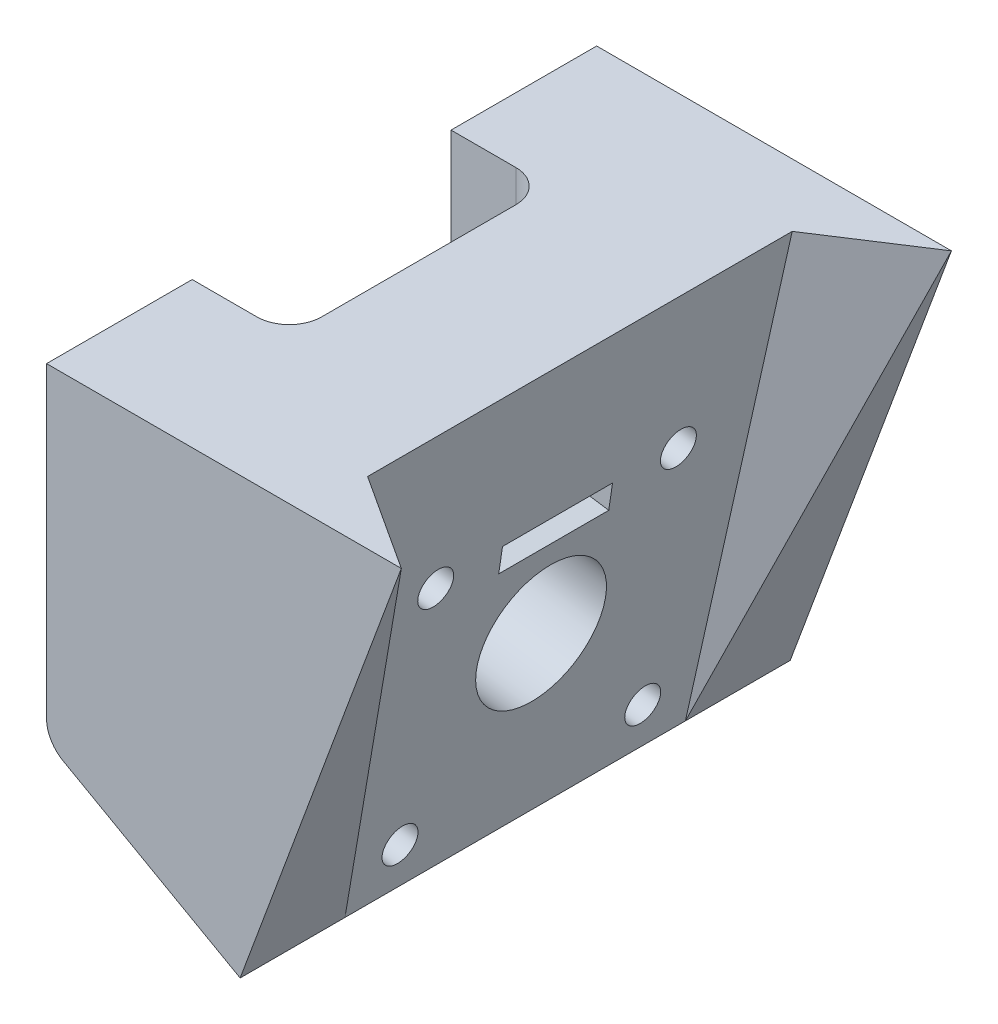
SolidWorks part; units mm, degrees
ref_plane "前视基准面" through (0, 0, 0) normal (0, 0, 1) x (1, 0, 0)
ref_plane "上视基准面" through (0, 0, 0) normal (0, 1, 0) x (1, 0, 0)
ref_plane "右视基准面" through (0, 0, 0) normal (1, 0, 0) x (0, 0, -1)
sketch "草图1" plane through (0, 0, 0) normal (0, 0, 1) x (1, 0, 0)
  line L1 (111.6207, -71.4575) -> (111.6207, -52.4486)
  line L2 (111.6207, -52.4486) -> (139.5487, -52.4486)
  line L4 (139.5487, -52.4486) -> (129.3649, -79.9481)
  line L6 (126.5093, -80.9969) -> (112.6407, -73.2009)
  arc A1 (126.5093, -80.9969) -> (129.3649, -79.9481) centre (127.4894, -79.2535) ccw
  arc A3 (111.6207, -71.4575) -> (112.6407, -73.2009) centre (113.6207, -71.4575) ccw
extrude "凸台-拉伸1" add sketch "草图1" along normal blind 34
sketch "草图2" plane through (0, -52.4486, 0) normal (0, 1, 0) x (1, 0, 0)
  line L0 (129.3649, -34) -> (129.3649, 0) construction
  line L1 (129.3649, -30) -> (129.3649, -4)
  line L3 (129.3649, -4) -> (139.5487, 0)
  line L5 (129.3649, -30) -> (139.5487, -34)
  line L6 (139.5487, -34) -> (139.5487, 0) construction
  line L7 (139.5487, -34) -> (139.5487, 0)
extrude "切除-拉伸1" cut sketch "草图2" against normal blind 34
ref_plane "基准面1" through (0, 0, 17) normal (0, 0, 1) x (1, 0, 0)
sketch "草图14" plane through (0, -52.4486, 0) normal (0, 1, 0) x (1, 0, 0)
  line L0 (111.6207, -17) -> (111.6207, -9)
  line L1 (111.6207, -9) -> (117.6207, -9)
  line L2 (117.6207, -9) -> (117.6207, -25)
  line L3 (117.6207, -25) -> (111.6207, -25)
  line L6 (111.6207, -34) -> (139.5487, -34)
  line L7 (139.5487, -34) -> (129.3649, -30)
  line L8 (129.3649, -30) -> (129.3649, -4)
  line L9 (129.3649, -4) -> (139.5487, 0)
  line L10 (139.5487, 0) -> (111.6207, 0)
  line L11 (111.6207, 0) -> (111.6207, -34)
  line L17 (111.6207, -9) -> (111.6207, -25)
  line M12 (111.6207, 0) -> (111.6207, -34)
  dimension "D1" = 0
extrude "切除-拉伸12" cut sketch "草图14" against normal through all contours L3 L2 L1 M12
fillet "圆角1" radius 2 2 edges at (117.6207, -64.2245, 25) (117.6207, -64.2245, 9)
sketch "草图15" plane through (0, 0, 34) normal (0, 0, 1) x (1, 0, 0)
  line L0 (129.3649, -79.9481) -> (139.5487, -52.4486) construction
  line L1 (129.3649, -79.9481) -> (139.5487, -52.4486)
  line L2 (139.5487, -52.4486) -> (133.5487, -52.4486)
  line L3 (139.5487, -52.4486) -> (111.6207, -52.4486) construction
  line L4 (133.5487, -52.4486) -> (124.3987, -77.1564)
  line L5 (112.6407, -73.2009) -> (126.5093, -80.9969) construction
  line L7 (121.5431, -78.2053) -> (126.5093, -80.9969)
  arc A0 (126.5093, -80.9969) -> (129.3649, -79.9481) centre (127.4894, -79.2535) ccw construction
  arc A1 (126.5093, -80.9969) -> (129.3649, -79.9481) centre (127.4894, -79.2535) ccw
  arc A2 (121.5431, -78.2053) -> (124.3987, -77.1564) centre (122.5232, -76.4619) ccw
  dimension "D1" = 2
extrude "切除-拉伸13" cut sketch "草图15" against normal through all
sketch "草图16" plane through (0, -52.4486, 0) normal (0, 1, 0) x (1, 0, 0)
  line L0 (124.3987, 0) -> (124.3987, -34) construction
  line L1 (124.3987, -5.9506) -> (124.3987, -28.0494)
  line L2 (129.3649, -4) -> (129.3649, -30) construction
  line L3 (129.3649, -4) -> (129.3649, -30)
  line L8 (129.3649, -4) -> (124.3987, -5.9506)
  line L9 (129.3649, -30) -> (124.3987, -28.0494)
extrude "切除-拉伸14" cut sketch "草图16" against normal through all
sketch "草图17" plane through (0, -52.4486, 0) normal (0, 1, 0) x (1, 0, 0)
  line L0 (124.3987, -5.9506) -> (124.3987, -28.0494) construction
  line L1 (124.3987, -5.9506) -> (124.3987, -28.0494)
  line L2 (133.5487, 0) -> (124.3987, -5.9506)
  line L3 (133.5487, -34) -> (124.3987, -28.0494)
  line L4 (133.5487, 0) -> (133.5487, -34)
extrude "切除-拉伸15" cut sketch "草图17" against normal through all
sketch "草图18" plane through (0, 0, 34) normal (0, 0, 1) x (1, 0, 0)
  line L0 (133.5487, -52.4486) -> (124.3987, -77.1564) construction
  line L1 (133.5487, -52.4486) -> (124.3987, -77.1564)
  line L4 (124.3987, -77.1564) -> (123.5852, -79.3532)
  line L5 (121.5431, -78.2053) -> (123.5852, -79.3532)
  arc A0 (121.5431, -78.2053) -> (124.3987, -77.1564) centre (122.5232, -76.4619) ccw construction
  arc A1 (121.5431, -78.2053) -> (124.3987, -77.1564) centre (122.5232, -76.4619) ccw
  arc M1 (121.5431, -78.2053) -> (124.3987, -77.1564) centre (122.5232, -76.4619) ccw
extrude "凸台-拉伸2" add sketch "草图18" against normal up to surface (34 mm away) contours L5 L4 M1 up to face at (119.2297, -67.619, 0)
sketch "草图21" plane through (0, -52.4486, 0) normal (0, 1, 0) x (1, 0, 0)
  line L0 (123.5852, 0) -> (123.5852, -34) construction
  line L1 (123.5852, -6.4797) -> (123.5852, -27.5203)
  line L6 (124.3987, -5.9506) -> (123.5852, -6.4797)
  line L7 (124.3987, -28.0494) -> (123.5852, -27.5203)
  line L8 (124.3987, -5.9506) -> (124.3987, -28.0494) construction
  line L9 (124.3987, -5.9506) -> (124.3987, -28.0494)
extrude "切除-拉伸16" cut sketch "草图21" against normal through all
sketch "草图22" plane through (0, 0, 17) normal (0, 0, 1) x (1, 0, 0)
  line L0 (133.5487, -52.4486) -> (123.5852, -52.4486) construction
  line L1 (127.5852, -52.4486) -> (123.5852, -52.4486)
  line L3 (123.5852, -52.4486) -> (127.5852, -52.4486)
  line L5 (123.5852, -79.3532) -> (123.5852, -52.4486) construction
  line L6 (123.5852, -79.3532) -> (123.5852, -52.4486)
  line L7 (123.5852, -52.4486) -> (127.5852, -52.4486)
  line L8 (127.5852, -52.4486) -> (123.5852, -79.3532)
extrude "凸台-拉伸3" add sketch "草图22" along normal up to surface and the other way up to surface contours L8 L1 L6 up to face at (126.9063, -61.4168, 29.6802) other way up to face at (126.9063, -61.4168, 4.3198)
extrude "切除-拉伸18" cut sketch "草图24" against normal blind 3.8
sketch "草图24" plane through (132.4551, -19.6926, -116.9432) normal (0.9891, -0.1471, 0) x (0, 0, -1)
  circle A8 centre (-141.4432, -57.7164) radius 1.1
  circle A9 centre (-126.4432, -57.7164) radius 1.1
  circle A10 centre (-141.4432, -42.7164) radius 1.1
  circle A11 centre (-126.4432, -42.7164) radius 1.1
extrude "切除-拉伸19" cut sketch "草图25" against normal blind 8
sketch "草图25" plane through (132.4551, -19.6926, -116.9432) normal (0.9891, -0.1471, 0) x (0, 0, -1)
  ellipse E1 centre (-133.9432, -49.4443) end of major axis (-131.9432, -49.4443) minor radius 1.9783
extrude "切除-拉伸20" cut sketch "草图26" against normal blind 3
sketch "草图26" plane through (132.4551, -19.6926, -116.9432) normal (0.9891, -0.1471, 0) x (0, 0, -1)
  line L8 (-137.3432, -42.5164) -> (-137.3432, -44.1164)
  line L9 (-130.5432, -42.5164) -> (-137.3432, -42.5164)
  line L10 (-130.5432, -44.1164) -> (-130.5432, -42.5164)
  line L11 (-137.3432, -44.1164) -> (-130.5432, -44.1164)
sketch "草图27" plane through (132.4551, -19.6926, 0) normal (0.9891, -0.1471, 0) x (0, 0, -1)
  circle A0 centre (-17, -49.4443) radius 4
  ellipse E0 centre (-17, -49.4443) end of major axis (-15, -49.4443) minor radius 1.9783 construction
  ellipse E1 centre (-17, -49.4443) end of major axis (-15, -49.4443) minor radius 1.9783
extrude "切除-拉伸21" cut sketch "草图27" against normal blind 5
